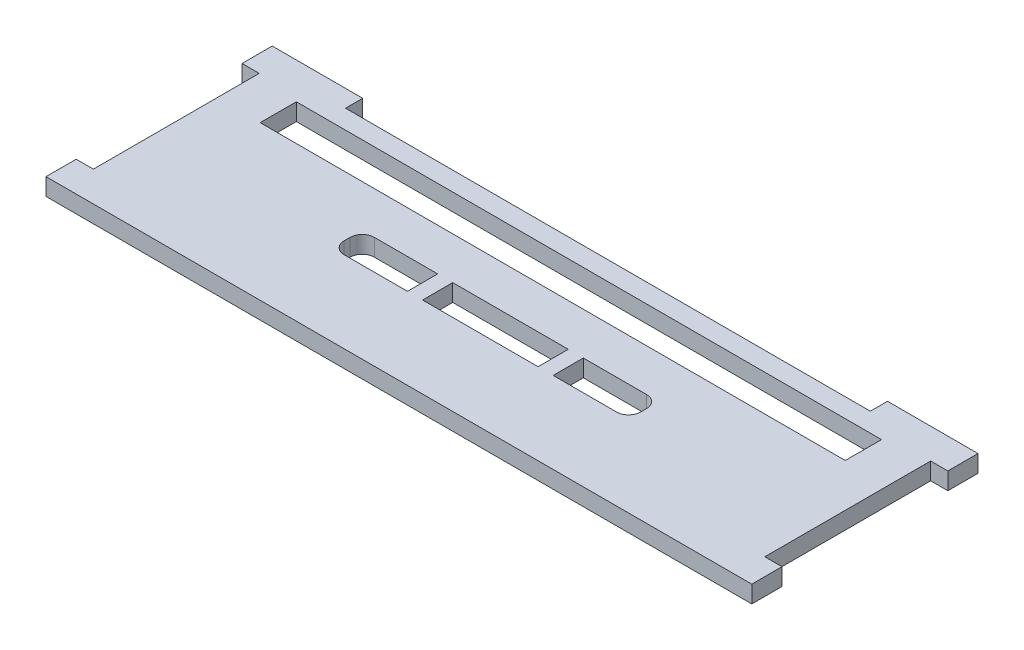
SolidWorks part; units mm, degrees
ref_plane "Front Plane" through (0, 0, 0) normal (0, 0, 1) x (1, 0, 0)
ref_plane "Top Plane" through (0, 0, 0) normal (0, 1, 0) x (1, 0, 0)
ref_plane "Right Plane" through (0, 0, 0) normal (1, 0, 0) x (0, 0, -1)
sketch "Sketch1" plane through (0, 0, 0) normal (0, 1, 0) x (1, 0, 0)
  line L1 (0, 0) -> (234, 0)
  line L2 (0, 0) -> (0, 75)
  line L3 (0, 75) -> (234, 75)
  line L4 (234, 0) -> (234, 75)
  dimension "D1" = 234
  dimension "D2" = 75
extrude "Boss-Extrude1" add sketch "Sketch1" along normal blind 5.7
sketch "Sketch2" plane through (0, 5.7, 0) normal (0, 1, 0) x (1, 0, 0)
  line L0 (0, 75) -> (0, 0) construction
  line L1 (0, 65) -> (5.7, 65)
  line L2 (0, 65) -> (0, 10)
  line L3 (0, 10) -> (5.7, 10)
  line L4 (5.7, 65) -> (5.7, 10)
  line L5 (0, 0) -> (234, 0) construction
  line L6 (234, 75) -> (0, 75) construction
  line L7 (234, 0) -> (234, 75) construction
  line L8 (234, 65) -> (228.3, 65)
  line L9 (234, 65) -> (234, 10)
  line L10 (234, 10) -> (228.3, 10)
  line L11 (228.3, 65) -> (228.3, 10)
  dimension "D1" = 10
  dimension "D2" = 10
  dimension "D3" = 5.7
  dimension "D4" = 10
  dimension "D5" = 10
  dimension "D6" = 5.7
extrude "Cut-Extrude1" cut sketch "Sketch2" against normal blind 5.7
sketch "Sketch3" plane through (0, 5.7, 0) normal (0, 1, 0) x (1, 0, 0)
  line L0 (234, 0) -> (234, 10) construction
  line L1 (214, 51) -> (20, 51)
  line L2 (214, 51) -> (214, 63)
  line L3 (214, 63) -> (20, 63)
  line L4 (20, 51) -> (20, 63)
  line L5 (234, 65) -> (234, 75) construction
  line L6 (0, 75) -> (0, 65) construction
  line L7 (234, 75) -> (0, 75) construction
  line L9 (136.15, 27) -> (97.85, 27)
  line L10 (136.15, 27) -> (136.15, 37)
  line L11 (136.15, 37) -> (97.85, 37)
  line L12 (97.85, 27) -> (97.85, 37)
  line L13 (92.85, 27) -> (71.85, 27)
  line L14 (92.85, 27) -> (92.85, 37)
  line L15 (92.85, 37) -> (71.85, 37)
  line L16 (67.85, 31) -> (67.85, 33)
  line L17 (162.15, 27) -> (141.15, 27)
  line L18 (166.15, 31) -> (166.15, 33)
  line L19 (162.15, 37) -> (141.15, 37)
  line L20 (141.15, 27) -> (141.15, 37)
  line L21 (0, 10) -> (0, 0) construction
  arc A0 (166.15, 31) -> (162.15, 27) centre (162.15, 31) cw
  arc A1 (166.15, 33) -> (162.15, 37) centre (162.15, 33) ccw
  arc A2 (67.85, 31) -> (71.85, 27) centre (71.85, 31) ccw
  arc A3 (67.85, 33) -> (71.85, 37) centre (71.85, 33) cw
  point P29 (166.15, 27)
  point P34 (67.85, 27)
  point P37 (67.85, 37)
  dimension "D17" = 4
  dimension "D1" = 20
  dimension "D2" = 20
  dimension "D3" = 12
  dimension "D4" = 12
  dimension "D5" = 67.85
  dimension "D6" = 67.85
  dimension "D7" = 38
  dimension "D8" = 38
  dimension "D9" = 38
  dimension "D10" = 25
  dimension "D11" = 25
  dimension "D12" = 5
  dimension "D13" = 5
  dimension "D14" = 10
  dimension "D15" = 10
  dimension "D16" = 10
extrude "Cut-Extrude2" cut sketch "Sketch3" against normal blind 5.7
sketch "Sketch4" plane through (0, 5.7, 0) normal (0, 1, 0) x (1, 0, 0)
  line L7 (234, 75) -> (0, 75) construction
  line L8 (30, 75) -> (204, 75)
  line L9 (30, 75) -> (30, 69.3)
  line L10 (30, 69.3) -> (204, 69.3)
  line L11 (204, 75) -> (204, 69.3)
  line L12 (0, 75) -> (0, 65) construction
  line L13 (234, 65) -> (234, 75) construction
  dimension "D4" = 30
  dimension "D5" = 30
  dimension "D6" = 5.7
extrude "Cut-Extrude3" cut sketch "Sketch4" against normal blind 5.7
sketch "Sketch6" plane through (0, 0, 0) normal (0, -1, 0) x (1, 0, 0)
  circle A0 centre (152, -66) radius 1.5
  circle A1 centre (82, -66) radius 1.5
  circle A2 centre (82, -43.5) radius 1.5
  circle A3 centre (152, -43.5) radius 1.5
  dimension "D1" = 3
  dimension "D2" = 3
  dimension "D3" = 3
  dimension "D4" = 3
extrude "Cut-Extrude4" cut sketch "Sketch6" against normal blind 3
sketch "Sketch7" plane through (0, 0, 0) normal (0, -1, 0) x (1, 0, 0)
  circle A0 centre (205, -66) radius 1.5
  circle A1 centre (160, -66) radius 1.5
  circle A2 centre (160, -46) radius 1.5
  circle A3 centre (205, -46) radius 1.5
  circle A4 centre (74, -66) radius 1.5
  circle A5 centre (29, -66) radius 1.5
  circle A6 centre (29, -46) radius 1.5
  circle A7 centre (74, -46) radius 1.5
  dimension "D1" = 3
  dimension "D2" = 3
  dimension "D3" = 3
  dimension "D4" = 3
  dimension "D5" = 3
  dimension "D6" = 3
  dimension "D7" = 3
  dimension "D8" = 3
extrude "Cut-Extrude5" cut sketch "Sketch7" against normal blind 3
